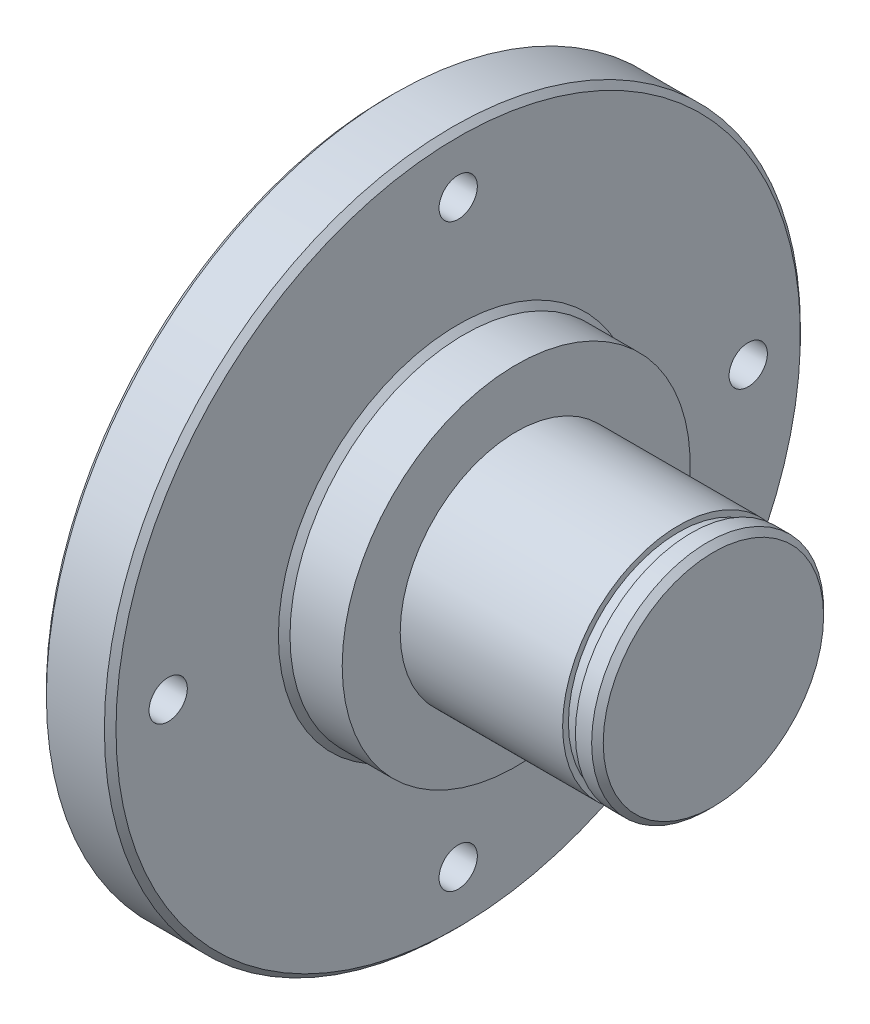
SolidWorks part; units mm, degrees
material "45"
ref_plane "前视基准面" through (0, 0, 0) normal (0, 0, 1) x (1, 0, 0)
ref_plane "上视基准面" through (0, 0, 0) normal (0, 1, 0) x (1, 0, 0)
ref_plane "右视基准面" through (0, 0, 0) normal (1, 0, 0) x (0, 0, -1)
sketch "草图1" plane through (0, 0, 0) normal (0, 0, 1) x (1, 0, 0)
  line L0 (-37.7137, 0) -> (71.7091, 0) construction
  line L1 (0, 0) -> (0, 30)
  line L2 (0, 30) -> (6, 30)
  line L3 (6, 30) -> (6, 15)
  line L4 (11, 10) -> (28, 10)
  line L5 (28, 10) -> (28, 0)
  line L6 (28, 0) -> (0, 0)
  line L7 (6, 15) -> (11, 15)
  line L8 (11, 15) -> (11, 10)
  dimension "D1" = 20
  dimension "D2" = 60
  dimension "D3" = 6
  dimension "D4" = 28
  dimension "D5" = 5
  dimension "D6" = 30
revolve "旋转1" add sketch "草图1" angle 360 about L0
sketch "草图2" plane through (0, 0, 0) normal (-1, 0, 0) x (0, 0, 1)
  circle A0 centre (0, 0) radius 25 construction
  point P8 (-25, 0)
  point P10 (0, 25)
  point P11 (25, 0)
  point P12 (0, -25)
  dimension "D1" = 50
hole_wizard "M4 螺纹孔1" positions "3D草图1" profile "草图3" tap size "M4" standard "Gb" end condition through all
sketch3d "3D草图1"
  point P18 (0, 0, -25)
  point P21 (0, 25, 0)
  point P24 (0, 0, 25)
  point P27 (0, -25, 0)
cosmetic thread "孔螺蚊线1" parameters "D2"=4
cosmetic thread "孔螺蚊线2" parameters "D2"=4
cosmetic thread "孔螺蚊线3" parameters "D2"=4
cosmetic thread "孔螺蚊线4" parameters "D2"=4
sketch "草图3" plane through (0, 0, -25) normal (0, 1, 0) x (0, 0, 1)
  line L0 (0, 0) -> (0, 28)
  line L1 (0, 28) -> (1.65, 28)
  line L2 (1.65, 28) -> (1.65, 0)
  line L5 (1.65, 0) -> (0, 0)
  line L11 (0, -6.35) -> (0, 107.95) construction
  dimension "通孔螺纹孔钻头直径" = 3.3
  dimension "通孔螺纹孔钻头深度" = 28
chamfer "倒角1" distance 0.5 angle 45 4 edges at (6, 0, 15) (28, 0, 10) (6, 0, 30) (0, 0, 30)
sketch "草图4" plane through (0, 0, 0) normal (0, 0, 1) x (1, 0, 0)
  line L0 (-5.3735, 0) -> (45.0235, 0) construction
  line L1 (26.1, 10.404) -> (25, 10.404)
  line L2 (26.1, 10.404) -> (26.1, 9.5)
  line L3 (26.1, 9.5) -> (25, 9.5)
  line L4 (25, 10.404) -> (25, 9.5)
  dimension "D1" = 14
  dimension "D2" = 1.1
  dimension "D3" = 19
revolve "切除-旋转1" cut sketch "草图4" angle 360 about L0
